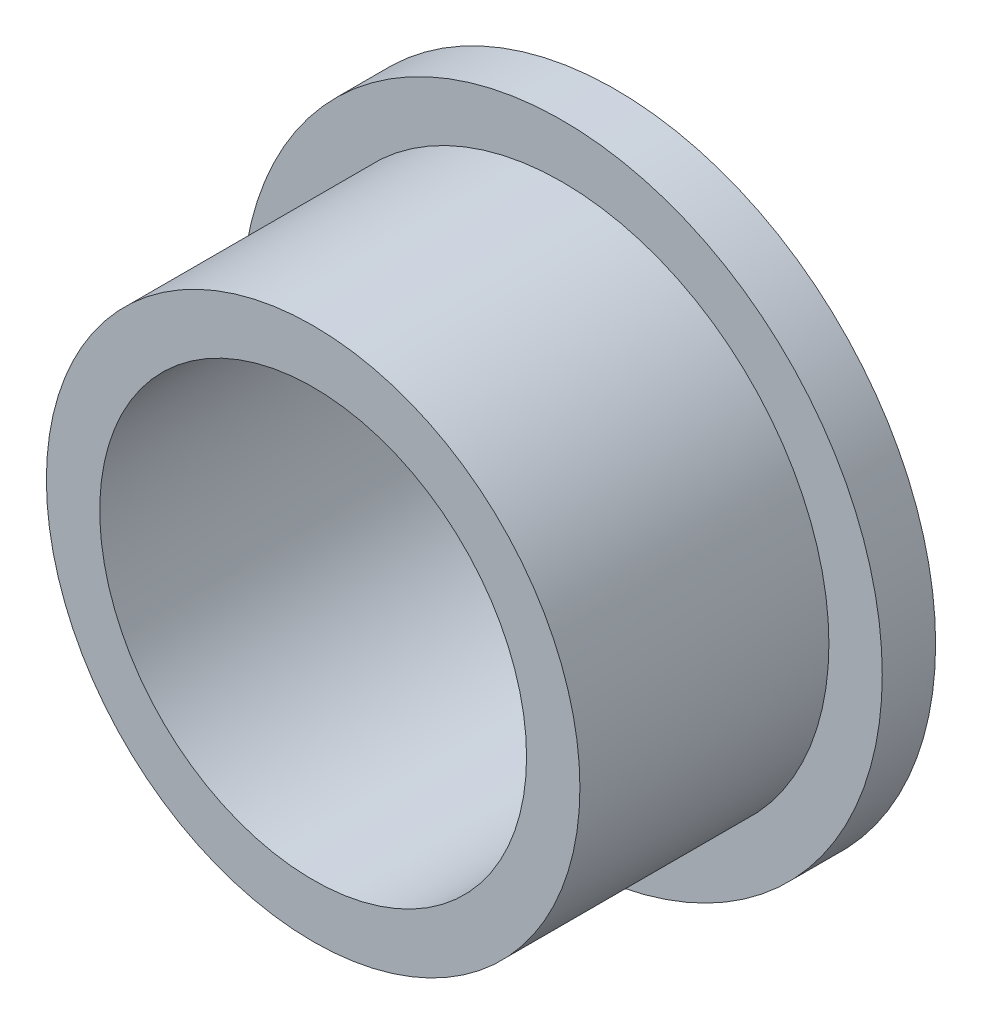
SolidWorks part; units mm, degrees
ref_plane "Front Plane" through (0, 0, 0) normal (0, 0, 1) x (1, 0, 0)
ref_plane "Top Plane" through (0, 0, 0) normal (0, 1, 0) x (1, 0, 0)
ref_plane "Right Plane" through (0, 0, 0) normal (1, 0, 0) x (0, 0, -1)
sketch "Sketch1" plane through (0, 0, 0) normal (0, 1, 0) x (1, 0, 0)
  line L0 (12, 0) -> (12, 17)
  line L1 (12, 17) -> (18, 17)
  line L2 (18, 17) -> (18, 14)
  line L3 (18, 14) -> (15, 14)
  line L4 (15, 14) -> (15, 0)
  line L7 (15, 0) -> (12, 0)
  line L8 (0, 0) -> (0, 17) construction
  dimension "D1" = 6
  dimension "D2" = 17
  dimension "D3" = 3
  dimension "D4" = 3
  dimension "D5" = 12
revolve "Revolve1" add sketch "Sketch1" angle 360 about L8
